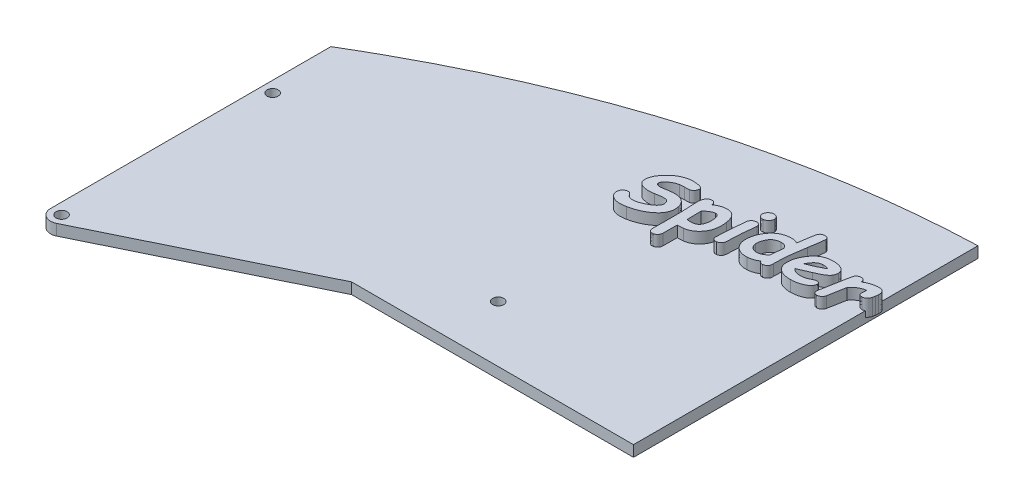
SolidWorks part; units mm, degrees
ref_plane "Front Plane" through (0, 0, 0) normal (0, 0, 1) x (1, 0, 0)
ref_plane "Top Plane" through (0, 0, 0) normal (0, 1, 0) x (1, 0, 0)
ref_plane "Right Plane" through (0, 0, 0) normal (1, 0, 0) x (0, 0, -1)
sketch "Sketch1" plane through (0, 0, 0) normal (0, 1, 0) x (1, 0, 0)
  line L0 (0, 0) -> (-266.16, 0) construction
  line L2 (-276.16, -130) -> (-276.16, 61.45) construction
  line L3 (-266.16, 61.45) -> (0, 0) construction
  line L4 (-266.16, -130) -> (0, 0) construction
  line L5 (-2.2496, -9.7437) -> (-268.4096, 51.7063) construction
  line L6 (-2.2496, -9.7437) -> (2.2496, 9.7437) construction
  line L7 (-268.4096, 51.7063) -> (-263.9104, 71.1937) construction
  line L8 (2.2496, 9.7437) -> (-263.9104, 71.1937) construction
  line L9 (-2.2496, -9.7437) -> (-263.9104, 71.1937) construction
  line L10 (-268.4096, 51.7063) -> (2.2496, 9.7437) construction
  line L11 (4.3888, -8.9855) -> (0, -11.1291) construction
  line L12 (4.3888, -8.9855) -> (-4.3888, 8.9855) construction
  line L13 (-261.7712, -138.9855) -> (-270.5488, -121.0145) construction
  line L14 (-4.3888, 8.9855) -> (-270.5488, -121.0145) construction
  line L15 (4.3888, -8.9855) -> (-270.5488, -121.0145) construction
  line L16 (-261.7712, -138.9855) -> (-4.3888, 8.9855) construction
  line L17 (-266.16, 61.45) -> (-266.16, -130) construction
  line L18 (-266.16, 61.45) -> (-266.16, -130) construction
  line L19 (-276.16, -130) -> (-256.16, -130) construction
  line L20 (-276.16, 61.45) -> (-256.16, 61.45) construction
  line L21 (-256.16, -130) -> (-256.16, 61.45) construction
  line L22 (-276.16, -130) -> (-256.16, 61.45) construction
  line L23 (-276.16, 61.45) -> (-256.16, -130) construction
  line L24 (-276.16, -130) -> (-276.16, 61.45)
  line L25 (-263.9104, 71.1937) -> (2.2496, 9.7437)
  line L26 (4.3888, -8.9855) -> (0, -11.1291)
  line L28 (0, -55) -> (0, 55) construction
  line L29 (0, -51.1291) -> (-81.8954, -51.1291)
  line L30 (-81.8954, -51.1291) -> (-261.7712, -138.9855) construction
  line L31 (-81.8954, -51.1291) -> (-261.7712, -138.9855)
  line L32 (0, -11.1291) -> (173.84, -11.1291)
  line L33 (173.84, -11.1291) -> (173.84, -51.1291)
  line L34 (173.84, -51.1291) -> (0, -51.1291)
  arc A0 (-276.16, 61.45) -> (-263.9104, 71.1937) centre (-266.16, 61.45) cw
  arc A1 (2.2496, 9.7437) -> (4.3888, -8.9855) centre (0, 0) cw
  arc A2 (-261.7712, -138.9855) -> (-276.16, -130) centre (-266.16, -130) cw
  circle A6 centre (-266.16, 61.45) radius 5
  circle A7 centre (0, 0) radius 5
  circle A8 centre (-266.16, -130) radius 5
  point P6 (-133.08, 30.725)
  point P7 (-133.08, -65)
  point P8 (-266.16, -34.275)
  dimension "D7" = 10
  dimension "D8" = 10
  dimension "D9" = 10
  dimension "D1" = 266.16
  dimension "D2" = 61.45
  dimension "D3" = 130
  dimension "D4" = 20
  dimension "D5" = 20
  dimension "D6" = 20
  dimension "D10" = 40
  dimension "D11" = 173.84
extrude "Boss-Extrude1" add sketch "Sketch1" along normal mid plane 10
sketch "Sketch3" plane through (0, 0, 0) normal (0, 1, 0) x (1, 0, 0)
  circle A0 centre (-266.16, 61.45) radius 5
  circle A1 centre (0, 0) radius 5
  circle A2 centre (-266.16, -130) radius 5
  dimension "D1" = 10
  dimension "D2" = 10
  dimension "D3" = 10
sketch "Sketch4" plane through (0, 5, 0) normal (0, 1, 0) x (1, 0, 0)
  text T0 "Spider" font "Comic Sans MS" height in points 72
extrude "Boss-Extrude2" [suppressed] add sketch "Sketch4" along normal blind 10
sketch "Sketch5" plane through (0, -5, 0) normal (0, -1, 0) x (1, 0, 0)
  line L0 (171.4917, 40.9944) -> (0, 40.9944) construction
  line L1 (0, -16.5) -> (0, 16.5) construction
  text T0 "Bot" font "Comic Sans MS" height in points 72
  point P2 (0, 38.768)
  point P5 (171.4917, 40.9944)
extrude "Boss-Extrude3" [suppressed] add sketch "Sketch5" along normal blind 10
sketch "Sketch6" plane through (0, 0, 0) normal (0, 1, 0) x (1, 0, 0)
  line L0 (-276.16, 61.45) -> (-276.16, 124.3124)
  line L1 (173.84, -11.1291) -> (173.84, 261.45)
  line L3 (-276.16, 61.45) -> (-263.9104, 71.1937)
  line L4 (-263.9104, 71.1937) -> (2.2496, 9.7437)
  line L5 (2.2496, 9.7437) -> (9.9354, 1.1348)
  line L6 (9.9354, 1.1348) -> (0, -11.1291)
  line L7 (0, -16.5) -> (0, 16.5) construction
  line L8 (0, -11.1291) -> (4.3888, -8.9855) construction
  line L9 (0, -11.1291) -> (173.84, -11.1291)
  arc A0 (4.3888, -8.9855) -> (2.2496, 9.7437) centre (0, 0) ccw construction
  spline S0 degree 2 poles (-276.16, 124.3124) (-60.1517, 253.2311) (173.84, 261.45) knots 0 0 0 0.880136 0.880136 0.880136
extrude "Boss-Extrude4" add sketch "Sketch6" along normal mid plane 10
sketch "Sketch7" plane through (0, 0, 0) normal (0, 1, 0) x (1, 0, 0)
  line L0 (173.84, -51.1291) -> (173.84, 261.45) construction
  spline S0 degree 3 poles (173.84, 140.7852) (95.2076, 145.4553) (-13.8876, 133.1842) (-86.2795, 98.6043) knots 0 0 0 0 1 1 1 1 construction
  text T0 "Spider" font "Comic Sans MS" height in points 169
  point P4 (173.84, 141.3252)
  point P5 (54.7654, 134.5942)
  point P8 (146.8266, 129.5125)
  point P9 (127.6986, 124.5939)
  point P10 (118.5358, 124.2091)
  point P11 (173.84, 140.7852)
extrude "Boss-Extrude5" add sketch "Sketch7" along normal blind 15
sketch "Sketch8" plane through (0, 0, 0) normal (0, 1, 0) x (1, 0, 0)
  spline S0 degree 3 poles (167.8428, 134.257) (140.1526, 133.8953) (76.359, 132.322) (12.9336, 123.875) (-22.1122, 115.0141) knots 0 0 0 0 0.434202 1 1 1 1 construction
  text T0 "Bot" font "Comic Sans MS" height in points 169
extrude "Boss-Extrude6" add sketch "Sketch8" against normal blind 15
